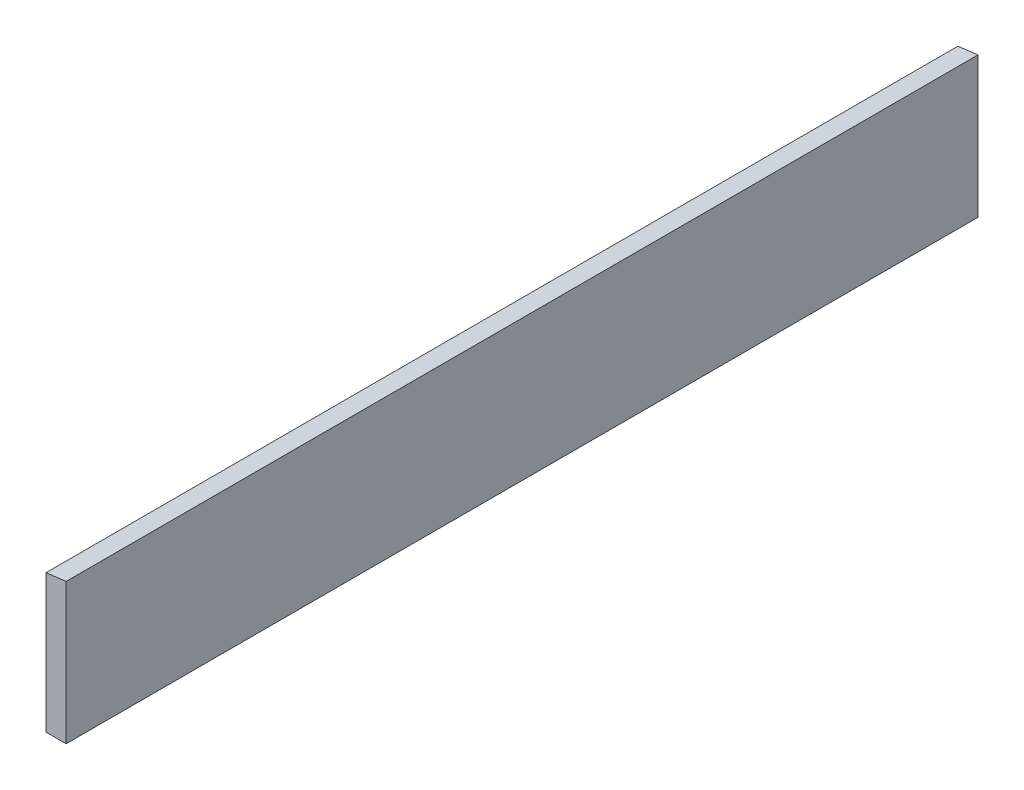
SolidWorks part; units mm, degrees
material "Pine"
ref_plane "Front Plane" through (0, 0, 0) normal (0, 0, 1) x (1, 0, 0)
ref_plane "Top Plane" through (0, 0, 0) normal (0, 1, 0) x (1, 0, 0)
ref_plane "Right Plane" through (0, 0, 0) normal (1, 0, 0) x (0, 0, -1)
sketch "Sketch1" plane through (0, 0, 0) normal (0, 0, 1) x (1, 0, 0)
  line L0 (232.7863, 27.1947) -> (486.7863, 27.1947)
  line L1 (486.7863, 27.1947) -> (486.7863, 179.5947)
  line L2 (486.7863, 179.5947) -> (79.2003, 128.6129)
  line L3 (232.7863, 128.6253) -> (232.7863, 27.1947)
  line L4 (486.7863, 160.3962) -> (81.5647, 109.7102)
  line L5 (251.8363, 131.0081) -> (251.8363, 27.1947)
  line L6 (467.7363, 158.0134) -> (251.8363, 131.0081) construction
  line L7 (467.7363, 27.1947) -> (467.7363, 158.0134)
  line L8 (251.8363, 46.2447) -> (467.7363, 46.2447) construction
  line L9 (251.8363, 131.0081) -> (251.8363, 46.2447) construction
  line L10 (467.7363, 46.2447) -> (467.7363, 158.0134) construction
  line L11 (486.7863, 160.3962) -> (484.4219, 179.2989)
  line L12 (486.7863, 27.1947) -> (486.7863, 179.5947) construction
  line L13 (486.7863, 179.5947) -> (232.7863, 147.8238) construction
  line L14 (81.5647, 109.7102) -> (60.2851, 279.8345) construction
  line L15 (232.7863, 147.8238) -> (232.7863, 27.1947) construction
  line L16 (81.5647, 109.7102) -> (79.2003, 128.6129)
  line L17 (484.4219, 179.2989) -> (230.4219, 147.528) construction
  line L22 (616.7284, 349.4357) -> (60.2851, 279.8345) construction
  line L23 (638.0079, 179.3114) -> (616.7284, 349.4357) construction
  line L24 (232.7863, 128.6253) -> (230.4219, 147.528) construction
extrude "Boss-Extrude1" add sketch "Sketch1" along normal blind 863.6 contours L7 L0 L1 L4
